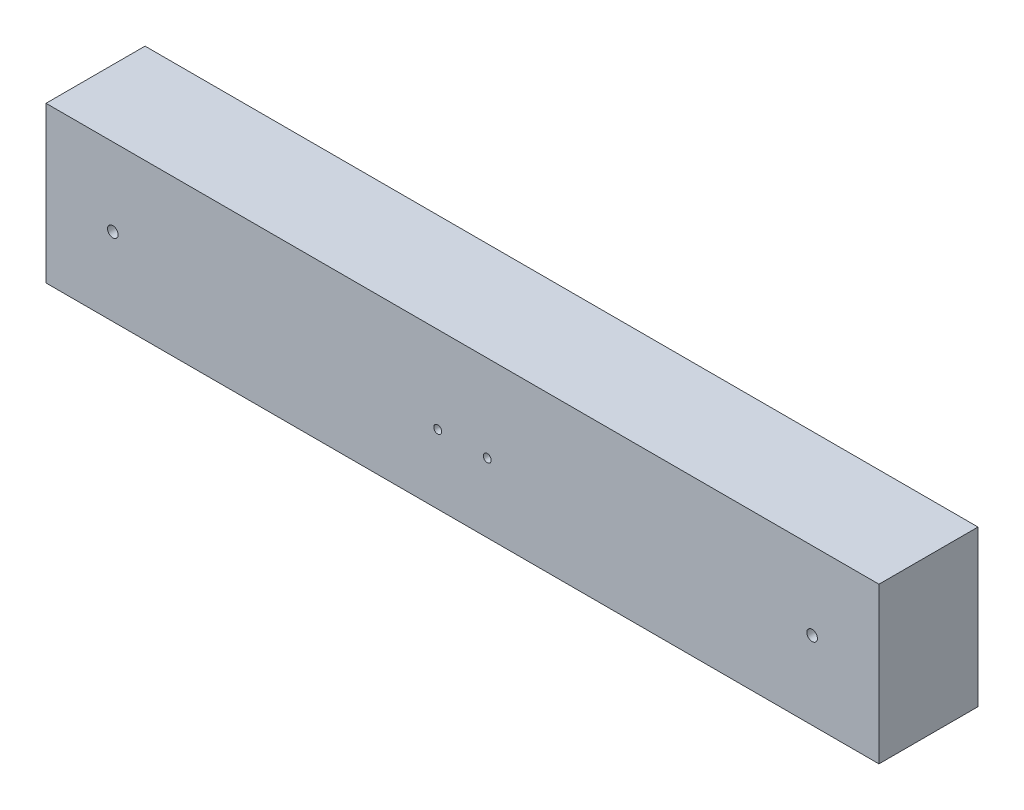
SolidWorks part; units mm, degrees
ref_plane "Front Plane" through (0, 0, 0) normal (0, 0, 1) x (1, 0, 0)
ref_plane "Top Plane" through (0, 0, 0) normal (0, 1, 0) x (1, 0, 0)
ref_plane "Right Plane" through (0, 0, 0) normal (1, 0, 0) x (0, 0, -1)
sketch "Sketch1" plane through (0, 0, 0) normal (0, 0, 1) x (1, 0, 0)
  line L1 (-373.8626, -69.85) -> (373.8626, -69.85)
  line L2 (-373.8626, -69.85) -> (-373.8626, 69.85)
  line L3 (-373.8626, 69.85) -> (373.8626, 69.85)
  line L4 (373.8626, -69.85) -> (373.8626, 69.85)
  line L5 (-373.8626, -69.85) -> (373.8626, 69.85) construction
  line L6 (-373.8626, 69.85) -> (373.8626, -69.85) construction
  point P0 (0, 0)
  dimension "D1" = 747.7252
  dimension "D2" = 139.7
extrude "Boss-Extrude1" add sketch "Sketch1" along normal blind 88.9
sketch "Sketch2" plane through (0, 0, 88.9) normal (0, 0, 1) x (1, 0, 0)
  line L1 (373.8626, 69.85) -> (-373.8626, 69.85) construction
  line L3 (-373.8626, 69.85) -> (-373.8626, -69.85) construction
  line L4 (373.8626, -69.85) -> (373.8626, 69.85) construction
  circle A0 centre (-313.8626, 0) radius 4.7625
  circle A1 centre (313.8626, 0) radius 4.7625
  dimension "D1" = 9.525
  dimension "D4" = 9.525
  dimension "D2" = 60
  dimension "D3" = 69.85
  dimension "D5" = 60
  dimension "D6" = 69.85
extrude "Cut-Extrude1" cut sketch "Sketch2" against normal through all
sketch "Sketch3" plane through (0, 0, 88.9) normal (0, 0, 1) x (1, 0, 0)
  line L0 (0, -69.85) -> (0, 69.85) construction
  line L1 (-373.8626, -69.85) -> (373.8626, -69.85) construction
  line L2 (373.8626, 69.85) -> (-373.8626, 69.85) construction
  line L3 (-28.575, -15.8242) -> (28.575, -15.8242)
  line L4 (-28.575, -15.8242) -> (-28.575, 0.0508)
  line L5 (-28.575, 0.0508) -> (28.575, 0.0508)
  line L6 (28.575, -15.8242) -> (28.575, 0.0508)
  circle A0 centre (-22.225, -7.8867) radius 3.5719
  circle A1 centre (22.225, -7.8867) radius 3.5719
  point P14 (-28.575, -7.8867)
  point P16 (0, 0.0508)
  dimension "D8" = 7.1437
  dimension "D9" = 7.1437
  dimension "D1" = 15.875
  dimension "D2" = 7.9375
  dimension "D3" = 44.45
  dimension "D4" = 6.35
  dimension "D5" = 57.15
  dimension "D6" = 77.7367
  dimension "D7" = 0
  dimension "D10" = 7.9375
extrude "Cut-Extrude2" cut sketch "Sketch3" against normal through all contours A0 | A1
